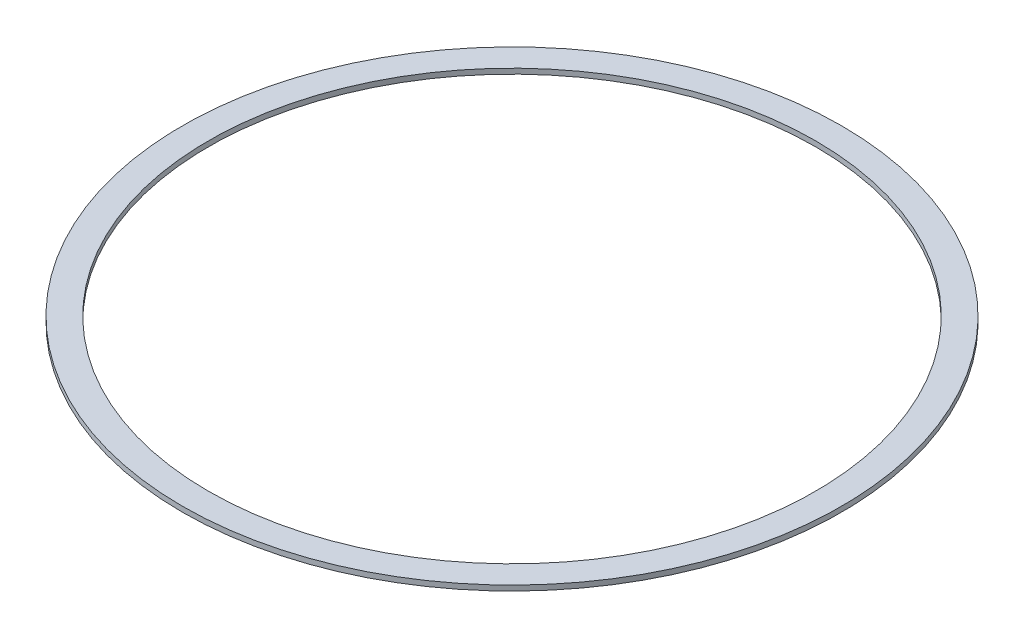
SolidWorks part; units mm, degrees
ref_plane "Front Plane" through (0, 0, 0) normal (0, 0, 1) x (1, 0, 0)
ref_plane "Top Plane" through (0, 0, 0) normal (0, 1, 0) x (1, 0, 0)
ref_plane "Right Plane" through (0, 0, 0) normal (1, 0, 0) x (0, 0, -1)
sketch "Sketch1" plane through (0, 0, 0) normal (0, 1, 0) x (1, 0, 0)
  line L0 (-175, 0) -> (175, 0) construction
  circle A0 centre (0, 0) radius 175
  circle A1 centre (0, 0) radius 190
  dimension "D1" = 350
  dimension "D2" = 380
extrude "Boss-Extrude1" add sketch "Sketch1" along normal mid plane 3
